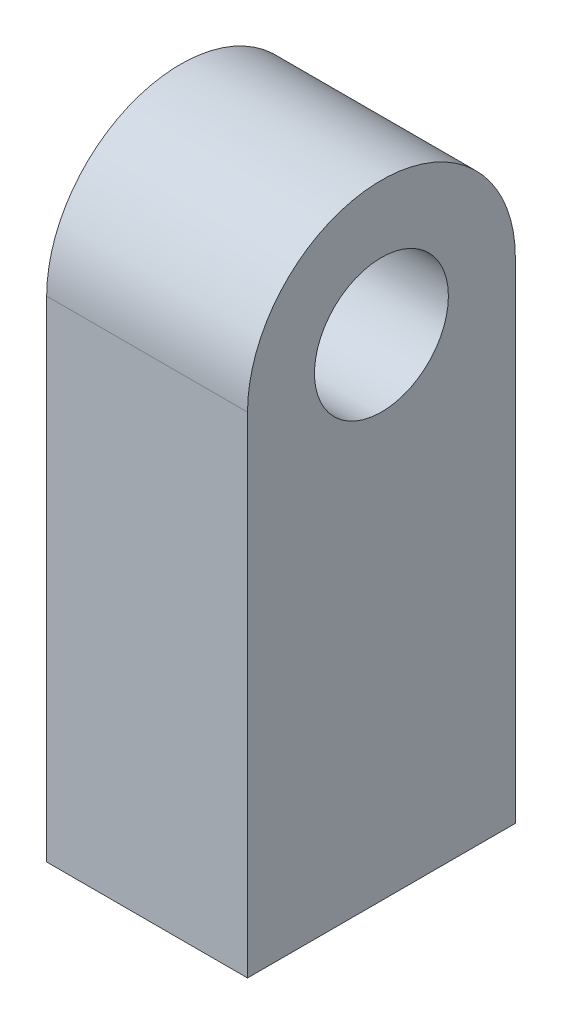
SolidWorks part; units mm, degrees
ref_plane "前视基准面" through (0, 0, 0) normal (0, 0, 1) x (1, 0, 0)
ref_plane "上视基准面" through (0, 0, 0) normal (0, 1, 0) x (1, 0, 0)
ref_plane "右视基准面" through (0, 0, 0) normal (1, 0, 0) x (0, 0, -1)
other "Configuration Table"
sketch "草图1" plane through (0, 0, 0) normal (0, 1, 0) x (1, 0, 0)
  line L1 (-4.5, -6) -> (4.5, -6)
  line L2 (-4.5, -6) -> (-4.5, 6)
  line L3 (-4.5, 6) -> (4.5, 6)
  line L4 (4.5, -6) -> (4.5, 6)
  line L5 (-4.5, -6) -> (4.5, 6) construction
  line L6 (-4.5, 6) -> (4.5, -6) construction
  point P0 (0, 0)
  dimension "D1" = 9
  dimension "D2" = 12
extrude "凸台-拉伸1" add sketch "草图1" along normal blind 28
sketch "草图2" plane through (4.5, 0, 0) normal (1, 0, 0) x (0, 0, -1)
  line L0 (0, -3.745) -> (0, 21.9586) construction
  line L1 (-6, -3.745) -> (-6, 21.9586)
  line L2 (6, -3.745) -> (6, 21.9586)
  line L3 (6, 28) -> (6, 0) construction
  arc A0 (-6, -3.745) -> (6, -3.745) centre (0, -3.745) ccw
  arc A1 (6, 21.9586) -> (-6, 21.9586) centre (0, 21.9586) ccw
  point P3 (0, 9.1068)
  point P8 (6, 19.1143)
  point P11 (0, 21.4162)
  point P12 (0, -3.745)
extrude "切除-拉伸1" cut sketch "草图2" against normal through all flip side to cut
sketch "草图3" plane through (0, 0, 0) normal (0, -1, 0) x (1, 0, 0)
  circle A0 centre (0, 0) radius 3
  dimension "D1" = 6
extrude "切除-拉伸2" cut sketch "草图3" against normal blind 10
sketch "草图4" plane through (4.5, 0, 0) normal (1, 0, 0) x (0, 0, -1)
  circle A0 centre (0, 21.9586) radius 3
  dimension "D1" = 6
extrude "切除-拉伸3" cut sketch "草图4" against normal through all
